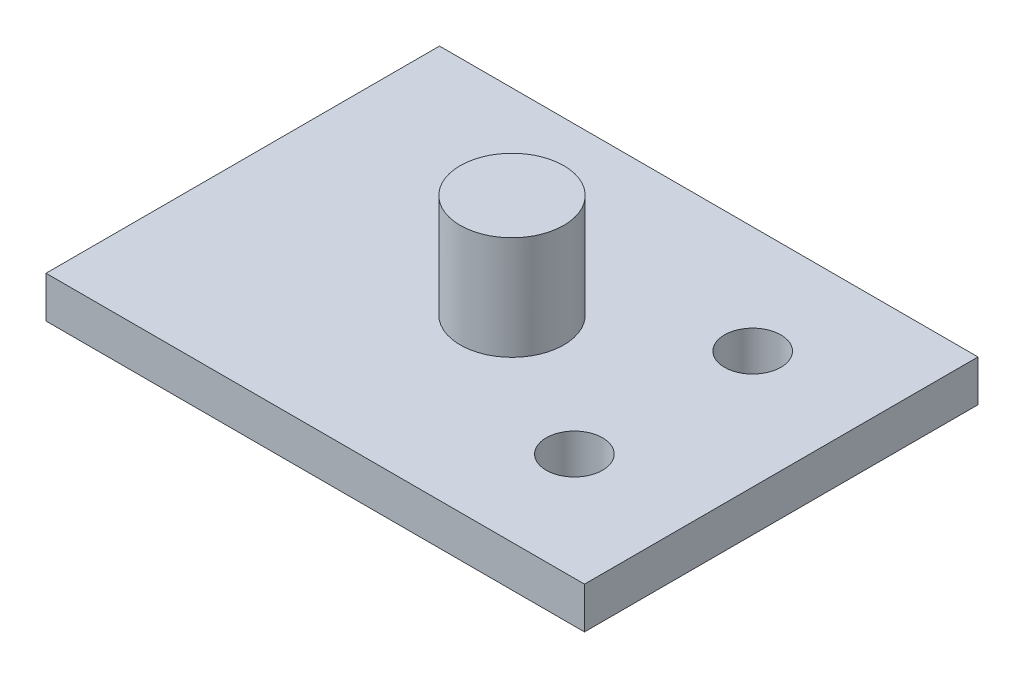
SolidWorks part; units mm, degrees
ref_plane "Front Plane" through (0, 0, 0) normal (0, 0, 1) x (1, 0, 0)
ref_plane "Top Plane" through (0, 0, 0) normal (0, 1, 0) x (1, 0, 0)
ref_plane "Right Plane" through (0, 0, 0) normal (1, 0, 0) x (0, 0, -1)
sketch "Sketch1" plane through (0, 0, 0) normal (0, 1, 0) x (1, 0, 0)
  line L1 (-16.51, -12.065) -> (16.51, -12.065)
  line L2 (-16.51, -12.065) -> (-16.51, 12.065)
  line L3 (-16.51, 12.065) -> (16.51, 12.065)
  line L4 (16.51, -12.065) -> (16.51, 12.065)
  line L5 (-16.51, -12.065) -> (16.51, 12.065) construction
  line L6 (-16.51, 12.065) -> (16.51, -12.065) construction
  point P0 (0, 0)
  dimension "D1" = 24.13
  dimension "D2" = 33.02
extrude "Boss-Extrude1" add sketch "Sketch1" along normal blind 2.54
sketch "Sketch2" plane through (0, 2.54, 0) normal (0, 1, 0) x (1, 0, 0)
  circle A0 centre (0, 0) radius 3.175
  point P2 (0, 0)
extrude "Boss-Extrude2" add sketch "Sketch2" along normal blind 6.35
sketch "Sketch3" plane through (0, 2.54, 0) normal (0, 1, 0) x (1, 0, 0)
  line L1 (16.51, 12.065) -> (-16.51, 12.065) construction
  line L2 (0, 0) -> (13.1894, 0) construction
  circle A0 centre (9.2915, 5.4667) radius 3.175
  circle A1 centre (9.2915, -5.4667) radius 3.175
  point P0 (9.2915, 5.4667)
  dimension "D1" = 6.5983
hole_wizard "#4 Clearance Hole1" positions "Sketch4" profile "Sketch6" hole size "#4" standard "ANSI Inch" end condition through all
sketch "Sketch4" plane through (0, 2.54, 0) normal (0, 1, 0) x (1, 0, 0)
  point P0 (9.2915, 5.4667)
  point P3 (9.2915, -5.4667)
sketch "Sketch6" plane through (9.2915, 2.54, -5.4667) normal (1, 0, 0) x (0, 0, 1)
  line L0 (0, 0) -> (0, 2.54)
  line L1 (0, 2.54) -> (1.7272, 2.54)
  line L2 (1.7272, 2.54) -> (1.7272, 0)
  line L5 (1.7272, 0) -> (0, 0)
  line L11 (0, -6.35) -> (0, 107.95) construction
  dimension "Thru Hole Dia." = 3.4544
  dimension "Thru Hole Depth" = 2.54
